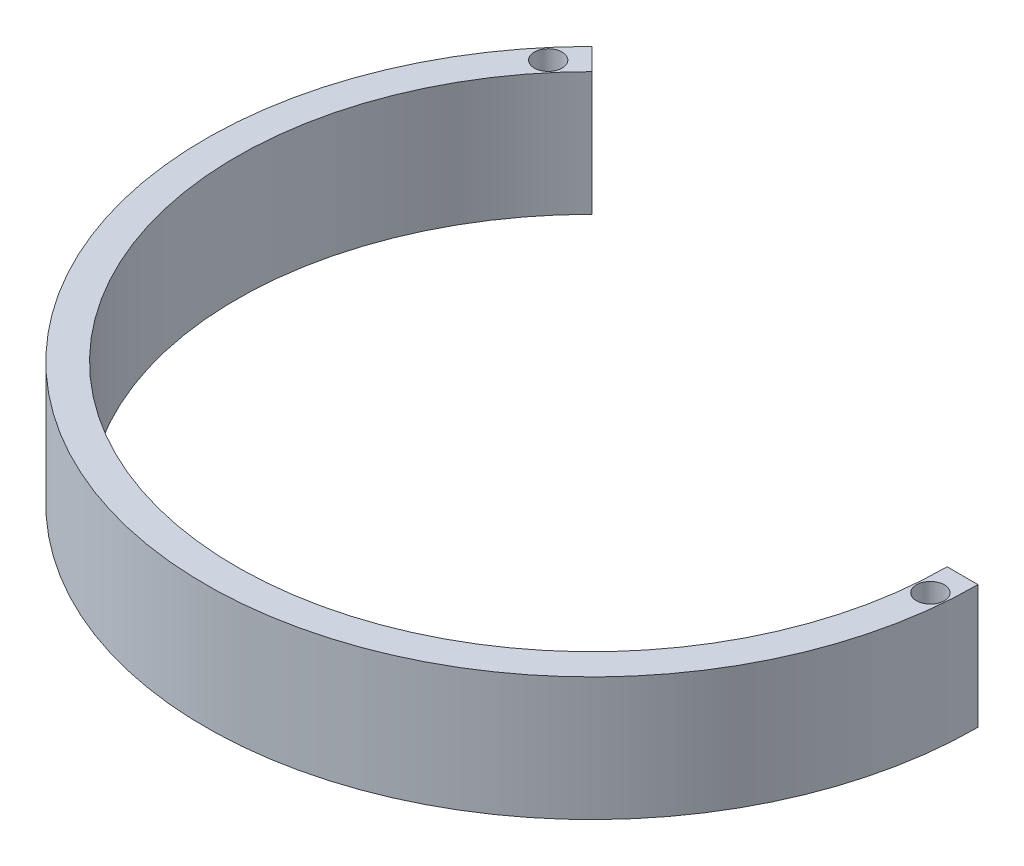
SolidWorks part; units mm, degrees
ref_plane "Front Plane" through (0, 0, 0) normal (0, 0, 1) x (1, 0, 0)
ref_plane "Top Plane" through (0, 0, 0) normal (0, 1, 0) x (1, 0, 0)
ref_plane "Right Plane" through (0, 0, 0) normal (1, 0, 0) x (0, 0, -1)
sketch "Sketch1" plane through (0, 0, 0) normal (0, 1, 0) x (1, 0, 0)
  line L0 (0, 0) -> (60, 0) construction
  line L1 (0, 0) -> (-42.4264, 42.4264) construction
  arc A0 (-42.4264, 42.4264) -> (60, 0) centre (0, 0) ccw
  dimension "D2" = 60
  dimension "D1" = 135
sketch "Sketch2" plane through (0, 0, 0) normal (0, 0, 1) x (0, 1, 0)
  line L0 (10, 62.5) -> (-10, 57.5) construction
  line L1 (-10, 62.5) -> (10, 62.5)
  line L2 (-10, 62.5) -> (-10, 57.5)
  line L3 (-10, 57.5) -> (10, 57.5)
  line L4 (10, 62.5) -> (10, 57.5)
  line L5 (0, -60) -> (0, 60) construction
  line L6 (0, -60) -> (0, 60) construction
  point P6 (0, 0)
  point P7 (0.6076, -10.8242)
  point P9 (0, 0)
  point P10 (2.5, 10.1431)
  point P12 (0, 60)
  dimension "D1" = 5
  dimension "D2" = 20
sweep "Sweep1" add profiles "Sketch2" path "Sketch1"
sketch "Sketch3" plane through (0, 10, 0) normal (0, 1, 0) x (1, 0, 0)
  line L1 (50, 0) -> (70, 0)
  line L2 (50, 0) -> (50, -10)
  line L3 (50, -10) -> (70, -10)
  line L4 (70, 0) -> (70, -10)
  point P4 (60, 0)
  dimension "D1" = 20
  dimension "D2" = 10
extrude "Boss-Extrude1" [suppressed] add sketch "Sketch3" along normal blind 5
sketch "Sketch4" [suppressed] plane through (0, 10, 0) normal (0, 1, 0) x (1, 0, 0)
  line L0 (-49.4975, 49.4975) -> (-35.3553, 35.3553)
  line L1 (-35.3553, 35.3553) -> (-42.4264, 28.2843)
  line L2 (-42.4264, 28.2843) -> (-56.5685, 42.4264)
  line L3 (-49.4975, 49.4975) -> (-56.5685, 42.4264)
  line L4 (0, 0) -> (-42.4264, 42.4264) construction
  line L5 (70, 0) -> (50, 0) construction
  line L6 (50, 0) -> (50, -10) construction
  point P8 (-42.4264, 42.4264)
  point P10 (-77.5135, 58.3122)
extrude "Boss-Extrude2" [suppressed] add sketch "Sketch4" along normal blind 5
sketch "Sketch6" plane through (0, -10, 0) normal (0, -1, 0) x (-1, 0, 0)
  line L0 (-62.5, 0) -> (-57.5, 0) construction
  line L1 (0, 0) -> (42.4264, 42.4264) construction
  arc A0 (-60, 0) -> (42.4264, 42.4264) centre (0, 0) ccw construction
  point P0 (-59.7913, -5)
  point P5 (45.8144, 38.7433)
  point P8 (-59.8267, -4.5564)
  dimension "D1" = 5
  dimension "D2" = 5
hole_wizard "M4 Clearance Hole1" positions "Sketch6" profile "Sketch7" hole size "M4" standard "ANSI Metric" end condition through all
sketch "Sketch7" plane through (59.7913, -10, 5) normal (1, 0, 0) x (0, 0, -1)
  line L0 (0, 0) -> (0, 20)
  line L1 (0, 20) -> (2.25, 20)
  line L2 (2.25, 20) -> (2.25, 0)
  line L5 (2.25, 0) -> (0, 0)
  line L11 (0, -6.35) -> (0, 107.95) construction
  dimension "Thru Hole Dia." = 4.5
  dimension "Thru Hole Depth" = 20
equation "\"D3@CirPattern1\"=\"D1@Sketch1\""
